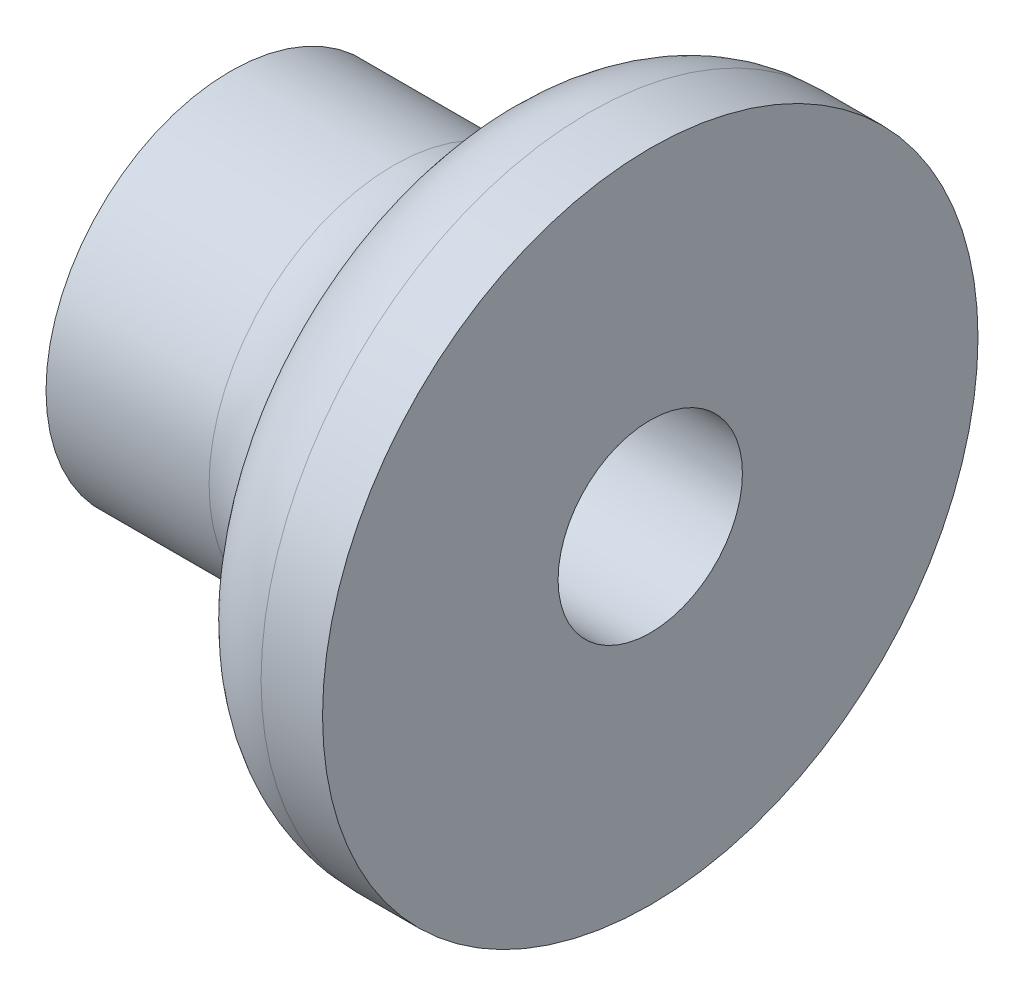
SolidWorks part; units mm, degrees
ref_plane "Front Plane" through (0, 0, 0) normal (0, 0, 1) x (1, 0, 0)
ref_plane "Top Plane" through (0, 0, 0) normal (0, 1, 0) x (1, 0, 0)
ref_plane "Right Plane" through (0, 0, 0) normal (1, 0, 0) x (0, 0, -1)
sketch "Sketch1" plane through (0, 0, 0) normal (1, 0, 0) x (0, 0, -1)
  circle A0 centre (0, 0) radius 4.5
  dimension "D1" = 9
extrude "Boss-Extrude1" add sketch "Sketch1" along normal blind 10.25
sketch "Sketch3" plane through (0, 0, 0) normal (-1, 0, 0) x (0, 0, 1)
  circle A0 centre (0, 0) radius 2.25
  dimension "D1" = 4.5
extrude "Cut-Extrude1" cut sketch "Sketch3" against normal blind 34
sketch "Sketch4" plane through (10.25, 0, 0) normal (1, 0, 0) x (0, 0, -1)
  circle A0 centre (0, 0) radius 8
  circle A1 centre (0, 0) radius 4.5 construction
  circle A2 centre (0, 0) radius 4.5
  dimension "D1" = 16
extrude "Boss-Extrude2" add sketch "Sketch4" against normal blind 4
fillet "Fillet1" radius 2.5 1 edges at (6.25, 0, -8)
fillet "Fillet2" radius 2.5 1 edges at (6.25, 0, -4.5)
